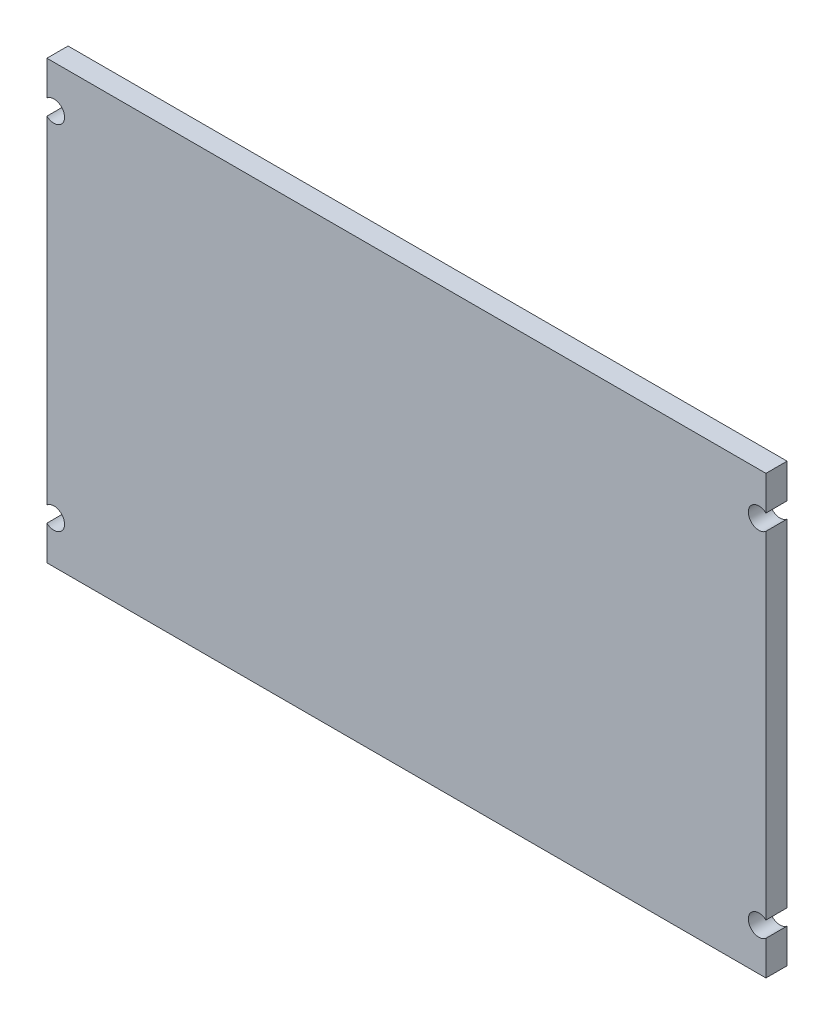
SolidWorks part; units mm, degrees
ref_plane "前视基准面" through (0, 0, 0) normal (0, 0, 1) x (1, 0, 0)
ref_plane "上视基准面" through (0, 0, 0) normal (0, 1, 0) x (1, 0, 0)
ref_plane "右视基准面" through (0, 0, 0) normal (1, 0, 0) x (0, 0, -1)
sketch "草图1" plane through (0, 0, 0) normal (0, 0, 1) x (1, 0, 0)
  line L1 (-51, -31) -> (51, -31)
  line L2 (-51, -31) -> (-51, 31)
  line L3 (-51, 31) -> (51, 31)
  line L4 (51, -31) -> (51, 31)
  line L5 (-51, -31) -> (51, 31) construction
  line L6 (-51, 31) -> (51, -31) construction
  point P0 (0, 0)
extrude "凸台-拉伸1" add sketch "草图1" along normal blind 3
sketch "草图2" plane through (0, 0, 3) normal (0, 0, 1) x (1, 0, 0)
  line L5 (-50, -25) -> (50, 25) construction
  line L6 (-50, 25) -> (50, -25) construction
  circle A0 centre (-50, 25) radius 1.5
  circle A1 centre (50, 25) radius 1.5
  circle A2 centre (50, -25) radius 1.5
  circle A3 centre (-50, -25) radius 1.5
  point P0 (0, 0)
extrude "切除-拉伸1" cut sketch "草图2" against normal blind 3
